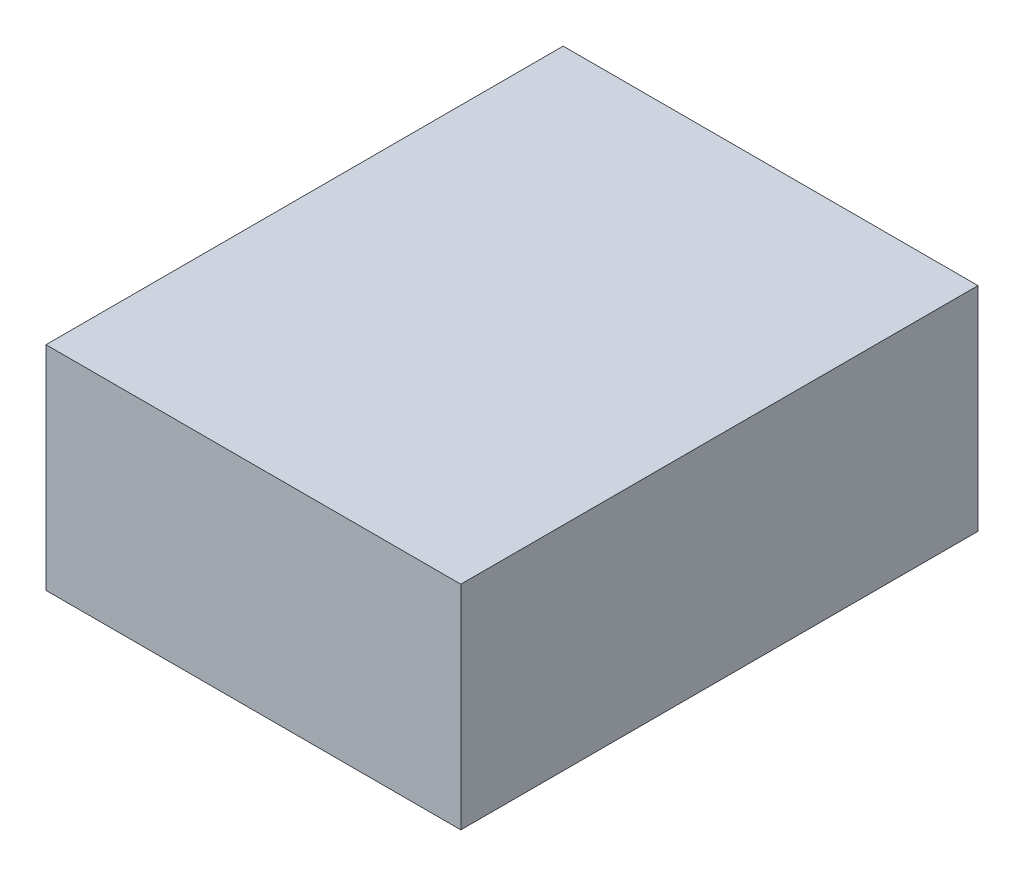
SolidWorks part; units mm, degrees
ref_plane "Front" through (0, 0, 0) normal (0, 0, 1) x (1, 0, 0)
ref_plane "Top" through (0, 0, 0) normal (0, 1, 0) x (1, 0, 0)
ref_plane "Right" through (0, 0, 0) normal (1, 0, 0) x (0, 0, -1)
sketch "Sketch1" plane through (0, 0, 0) normal (0, 0, 1) x (1, 0, 0)
  line L1 (0, 0) -> (7.7, 0)
  line L2 (0, 0) -> (0, 3.95)
  line L3 (0, 3.95) -> (7.7, 3.95)
  line L4 (7.7, 0) -> (7.7, 3.95)
  dimension "D1" = 3.95
  dimension "D2" = 7.7
extrude "Boss-Extrude1" add sketch "Sketch1" along normal blind 9.6
